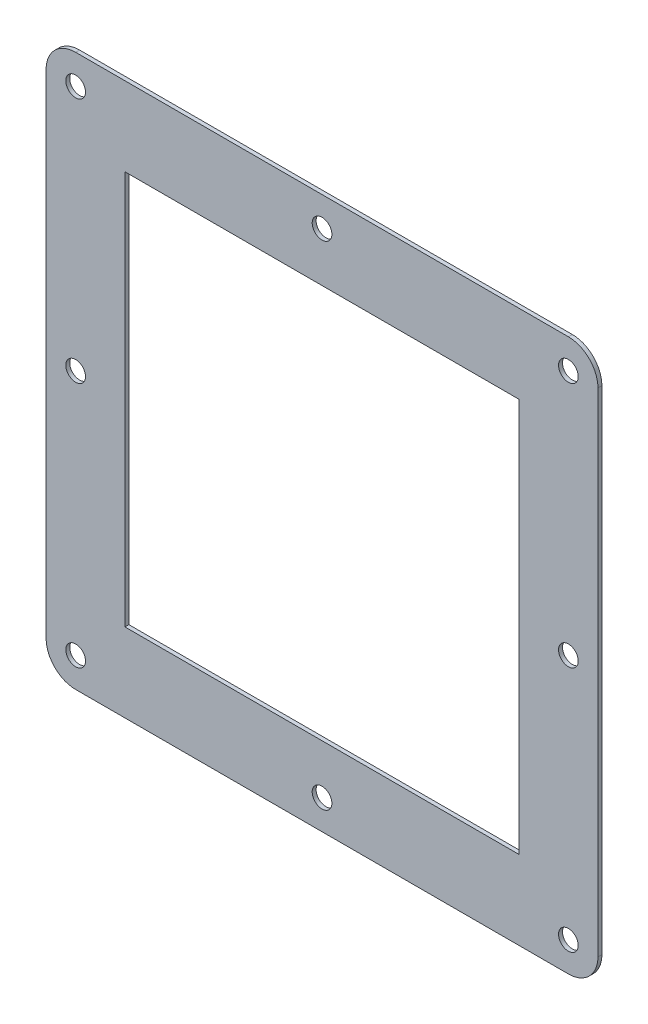
SolidWorks part; units mm, degrees
ref_plane "Front Plane" through (0, 0, 0) normal (0, 0, 1) x (1, 0, 0)
ref_plane "Top Plane" through (0, 0, 0) normal (0, 1, 0) x (1, 0, 0)
ref_plane "Right Plane" through (0, 0, 0) normal (1, 0, 0) x (0, 0, -1)
sketch "Sketch2" plane through (0, 0, 0) normal (0, 0, 1) x (1, 0, 0)
  line L0 (-125, 125) -> (125, 125) construction
  line L1 (-125, 140) -> (125, 140)
  line L2 (-140, 125) -> (-140, -125)
  line L3 (-125, -140) -> (125, -140)
  line L4 (140, 125) -> (140, -125)
  line L5 (-140, 140) -> (140, -140) construction
  line L6 (-140, -140) -> (140, 140) construction
  line L7 (125, 125) -> (125, -125) construction
  line L8 (125, -125) -> (-125, -125) construction
  line L9 (-125, -125) -> (-125, 125) construction
  arc A0 (-140, -125) -> (-125, -140) centre (-125, -125) ccw
  arc A1 (125, -140) -> (140, -125) centre (125, -125) ccw
  arc A2 (125, 140) -> (140, 125) centre (125, 125) cw
  arc A3 (-125, 140) -> (-140, 125) centre (-125, 125) ccw
  circle A4 centre (-125, 125) radius 5
  circle A5 centre (0, 125) radius 5
  circle A6 centre (125, 125) radius 5
  circle A13 centre (0, 0) radius 4
  circle A14 centre (125, 0) radius 5
  circle A15 centre (-125, 0) radius 5
  circle A16 centre (-125, -125) radius 5
  circle A17 centre (0, -125) radius 5
  circle A18 centre (125, -125) radius 5
  point P0 (0, 0)
  dimension "D3" = 15
  dimension "D4" = 10
  dimension "D5" = 10
  dimension "D6" = 10
  dimension "D7" = 8
  dimension "D8" = 10
  dimension "D9" = 10
  dimension "D10" = 10
  dimension "D11" = 10
  dimension "D1" = 280
  dimension "D2" = 280
extrude "Boss-Extrude1" add sketch "Sketch2" along normal blind 2
sketch "Sketch3" plane through (0, 0, 2) normal (0, 0, 1) x (1, 0, 0)
  line L1 (-100, 100) -> (100, 100)
  line L2 (-100, 100) -> (-100, -100)
  line L3 (-100, -100) -> (100, -100)
  line L4 (100, 100) -> (100, -100)
  line L5 (-100, 100) -> (100, -100) construction
  line L6 (-100, -100) -> (100, 100) construction
  point P0 (0, 0)
  dimension "D1" = 200
  dimension "D2" = 200
extrude "Cut-Extrude1" cut sketch "Sketch3" against normal blind 10
